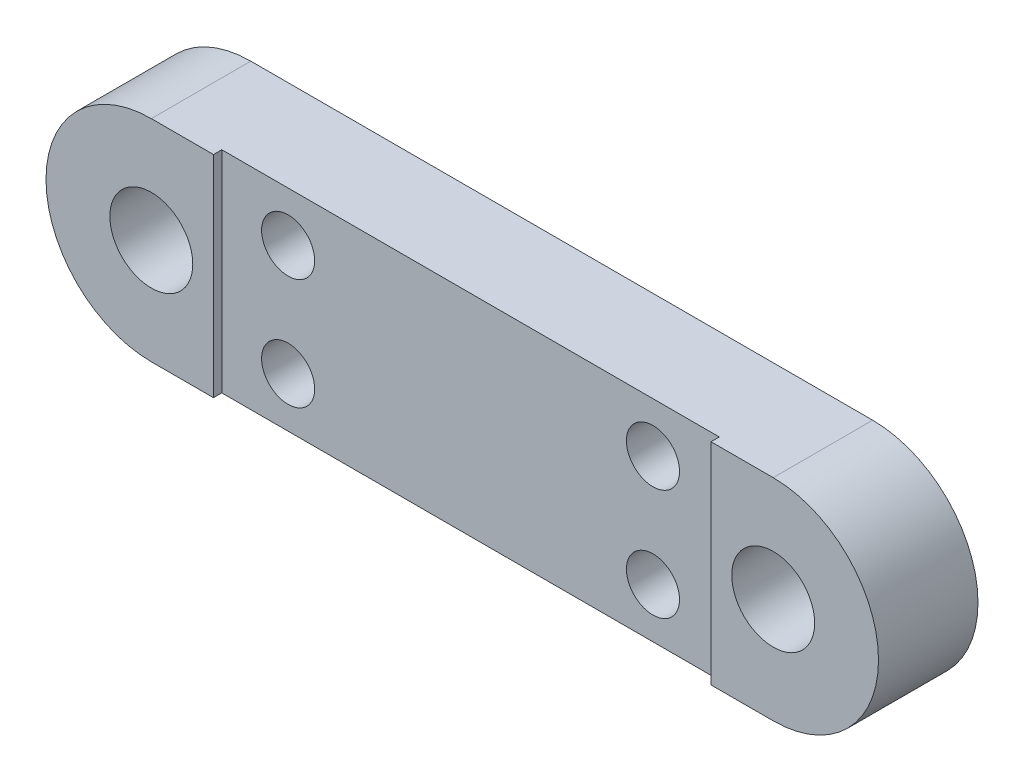
SolidWorks part; units mm, degrees
ref_plane "Alzado" through (0, 0, 0) normal (0, 0, 1) x (1, 0, 0)
ref_plane "Planta" through (0, 0, 0) normal (0, 1, 0) x (1, 0, 0)
ref_plane "Vista lateral" through (0, 0, 0) normal (1, 0, 0) x (0, 0, -1)
sketch "Croquis1" plane through (0, 0, 0) normal (0, 0, 1) x (1, 0, 0)
  line L0 (0, 0) -> (75, 0) construction
  line L1 (0, 12.7) -> (75, 12.7)
  line L2 (0, -12.7) -> (75, -12.7)
  arc A0 (0, 12.7) -> (0, -12.7) centre (0, 0) ccw
  arc A1 (75, -12.7) -> (75, 12.7) centre (75, 0) ccw
  circle A2 centre (0, 0) radius 5
  circle A3 centre (75, 0) radius 5
  point P3 (37.5, 0)
  dimension "D3" = 10
  dimension "D4" = 10
  dimension "D1" = 75
  dimension "D2" = 25.4
extrude "Saliente-Extruir1" add sketch "Croquis1" along normal blind 12
sketch "Croquis2" plane through (0, -12.7, 0) normal (0, -1, 0) x (1, 0, 0)
  line L0 (37.5, 12) -> (37.5, 0) construction
  line L1 (0, 12) -> (75, 12) construction
  line L2 (0, 0) -> (75, 0) construction
  circle A0 centre (37.5, 6) radius 4
  dimension "D1" = 8
extrude "Cortar-Extruir1" cut sketch "Croquis2" against normal blind 21
sketch "Croquis3" plane through (0, 0, 12) normal (0, 0, 1) x (1, 0, 0)
  line L0 (37.5, 12.7) -> (37.5, -12.7) construction
  line L1 (75, 12.7) -> (0, 12.7) construction
  line L2 (0, -12.7) -> (75, -12.7) construction
  line L4 (7.5, -17) -> (67.5, -17)
  line L5 (7.5, -17) -> (7.5, 17)
  line L6 (7.5, 17) -> (67.5, 17)
  line L7 (67.5, -17) -> (67.5, 17)
  line L8 (7.5, -17) -> (67.5, 17) construction
  line L9 (7.5, 17) -> (67.5, -17) construction
  point P6 (37.5, 0)
  dimension "D1" = 60
  dimension "D2" = 34
extrude "Cortar-Extruir4" cut sketch "Croquis3" against normal blind 1
sketch "Croquis5" plane through (0, 0, 12) normal (0, 0, 1) x (1, 0, 0)
  circle A0 centre (59.5, -6.7) radius 3.2
  circle A1 centre (59.5, 6.7) radius 3.2
  circle A2 centre (15.5, 6.7) radius 3.2
  circle A3 centre (15.5, -6.7) radius 3.2
  dimension "D1" = 6.4
  dimension "D2" = 6.4
  dimension "D3" = 6.4
  dimension "D4" = 6.4
extrude "Cortar-Extruir5" cut sketch "Croquis5" against normal through all
